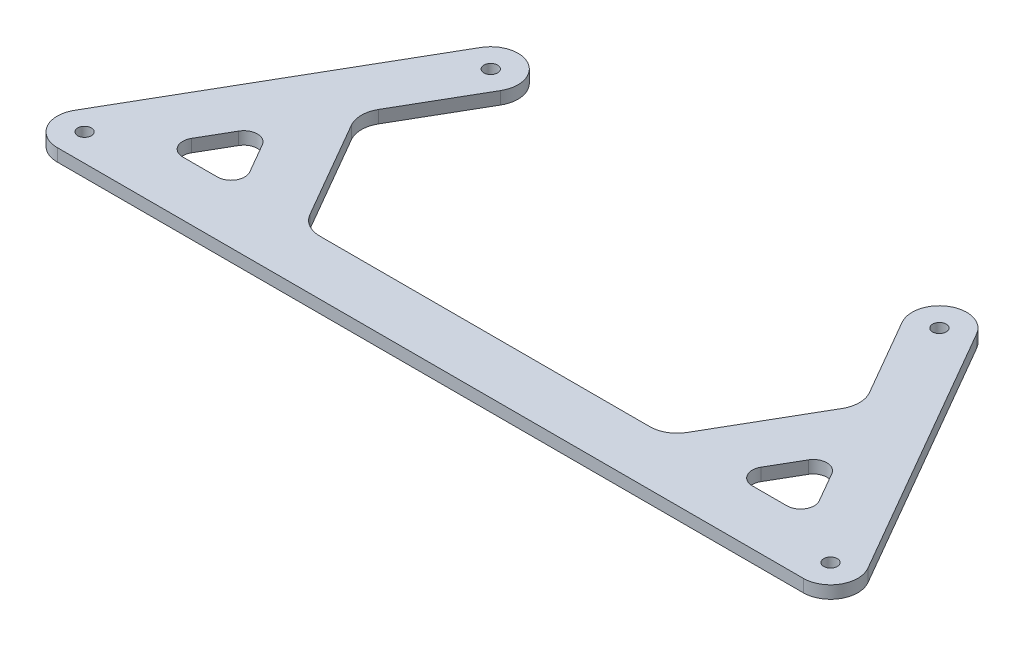
SolidWorks part; units mm, degrees
ref_plane "Front Plane" through (0, 0, 0) normal (0, 0, 1) x (1, 0, 0)
ref_plane "Top Plane" through (0, 0, 0) normal (0, 1, 0) x (1, 0, 0)
ref_plane "Right Plane" through (0, 0, 0) normal (1, 0, 0) x (0, 0, -1)
sketch "Sketch1" plane through (0, 0, 0) normal (0, 1, 0) x (1, 0, 0)
  line L0 (173.5081, 0) -> (-173.5081, 0) construction
  line L1 (0, -54.9415) -> (0, 54.9415) construction
  line L2 (-173.5081, 0) -> (-104.352, 119.7818) construction
  line L3 (-115.3506, 126.1318) -> (-184.5066, 6.35)
  line L4 (-93.3535, 113.4318) -> (-117.7964, 71.0956)
  line L5 (173.5081, 0) -> (104.352, 119.7818) construction
  line L6 (151.5111, 12.7) -> (113.4111, 12.7)
  line L7 (115.3506, 126.1318) -> (184.5066, 6.35)
  line L8 (-132.4611, 45.6956) -> (-113.4111, 12.7)
  line L9 (-173.5081, -12.7) -> (173.5081, -12.7)
  line L10 (-151.5111, 12.7) -> (-113.4111, 12.7)
  line L11 (-117.7964, 71.0956) -> (-84.0817, 12.7)
  line L12 (-132.4611, 45.6956) -> (-151.5111, 12.7)
  line L13 (-84.0817, 12.7) -> (84.0817, 12.7)
  line L14 (132.4611, 45.6956) -> (113.4111, 12.7)
  line L15 (132.4611, 45.6956) -> (151.5111, 12.7)
  line L16 (117.7964, 71.0956) -> (84.0817, 12.7)
  line L17 (93.3535, 113.4318) -> (117.7964, 71.0956)
  circle A0 centre (-173.5081, 0) radius 3.175
  circle A1 centre (-104.352, 119.7818) radius 3.175
  arc A2 (-93.3535, 113.4318) -> (-115.3506, 126.1318) centre (-104.352, 119.7818) ccw
  arc A3 (-184.5066, 6.35) -> (-173.5081, -12.7) centre (-173.5081, 0) ccw
  arc A4 (184.5066, 6.35) -> (173.5081, -12.7) centre (173.5081, 0) cw
  arc A5 (93.3535, 113.4318) -> (115.3506, 126.1318) centre (104.352, 119.7818) cw
  circle A6 centre (104.352, 119.7818) radius 3.175
  circle A7 centre (173.5081, 0) radius 3.175
  point P4 (0, 0)
  point P9 (0, 0)
  point P28 (0, 12.7)
  dimension "D2" = 6.35
  dimension "D5" = 6.35
  dimension "D6" = 25.4
  dimension "D7" = 25.4
  dimension "D1" = 347.0162
  dimension "D3" = 60
  dimension "D4" = 138.3121
  dimension "D8" = 38.1
  dimension "D9" = 38.1
  dimension "D10" = 25.4
extrude "Boss-Extrude1" add sketch "Sketch1" along normal blind 5.842
fillet "Fillet1" radius 6.35 6 edges at (132.4611, 2.921, -45.6956) (113.4111, 2.921, -12.7) (151.5111, 2.921, -12.7) (-113.4111, 2.921, -12.7) (-151.5111, 2.921, -12.7) (-132.4611, 2.921, -45.6956)
fillet "Fillet2" radius 12.7 4 edges at (-117.7964, 2.921, -71.0956) (117.7964, 2.921, -71.0956) (84.0817, 2.921, -12.7) (-84.0817, 2.921, -12.7)
